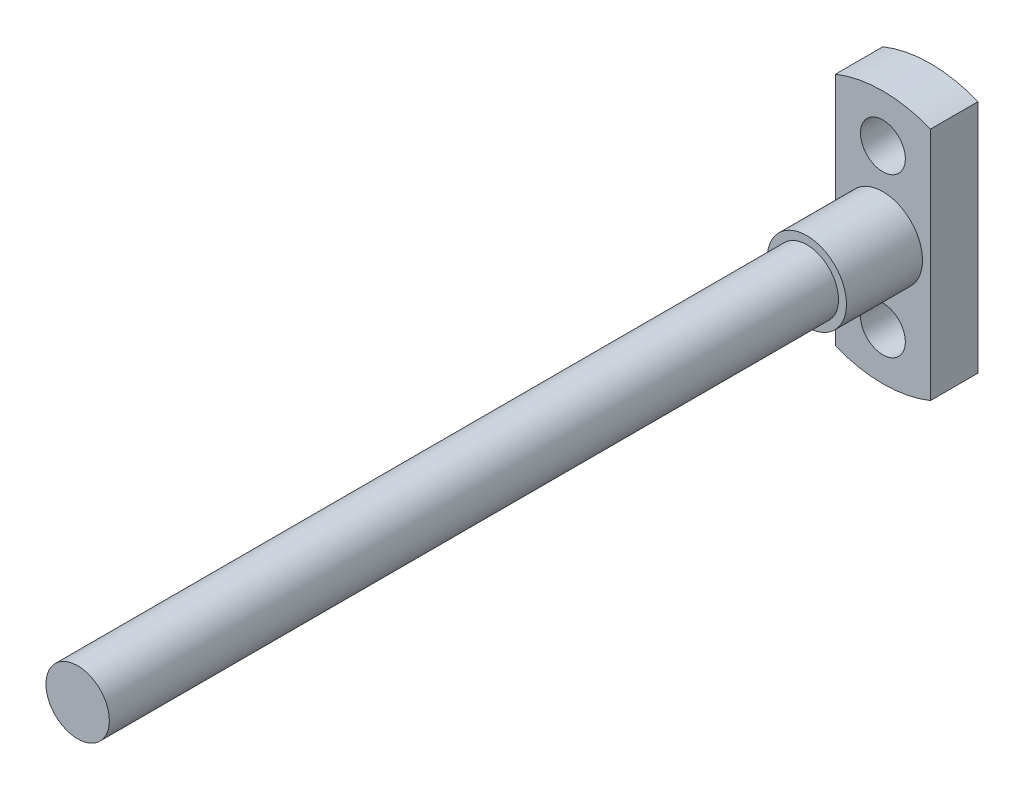
SolidWorks part; units mm, degrees
ref_plane "Front Plane" through (0, 0, 0) normal (0, 0, 1) x (1, 0, 0)
ref_plane "Top Plane" through (0, 0, 0) normal (0, 1, 0) x (1, 0, 0)
ref_plane "Right Plane" through (0, 0, 0) normal (1, 0, 0) x (0, 0, -1)
sketch "Sketch1" plane through (0, 0, 0) normal (0, 0, 1) x (1, 0, 0)
  line L0 (0, 0) -> (9.525, 23.5464) construction
  line L2 (0, 0) -> (0, 23.5464)
  line L4 (9.525, 0) -> (9.525, 23.5464)
  arc A0 (0, 23.5464) -> (9.525, 23.5464) centre (4.7625, 11.7732) cw
  arc A1 (9.525, 0) -> (0, 0) centre (4.7625, 11.7732) cw
  dimension "D1" = 12.7
  dimension "D2" = 9.525
extrude "Boss-Extrude1" add sketch "Sketch1" along normal blind 4.7625
sketch "Sketch2" plane through (0, 0, 4.7625) normal (0, 0, 1) x (1, 0, 0)
  line L0 (0, 23.5464) -> (9.525, 0) construction
  circle A0 centre (4.7625, 11.7732) radius 3.9688
  dimension "D1" = 7.9375
extrude "Boss-Extrude2" add sketch "Sketch2" along normal blind 7.62
sketch "Sketch3" plane through (0, 0, 12.3825) normal (0, 0, 1) x (1, 0, 0)
  circle A0 centre (4.7625, 11.7732) radius 3.175
  dimension "D1" = 6.35
extrude "Boss-Extrude3" add sketch "Sketch3" along normal blind 73.025
hole_wizard "#16 (0.177) Diameter Hole1" positions "Sketch5" profile "Sketch6" hole size "#16" standard "ANSI Inch" end condition through all
sketch "Sketch5" plane through (0, 0, 4.7625) normal (0, 0, 1) x (1, 0, 0)
  line L0 (4.7625, 24.4732) -> (4.7625, -0.9268) construction
  line L4 (0, 11.7732) -> (9.1829, 11.7732) construction
  line L5 (0, 23.5464) -> (0, 0) construction
  arc A1 (9.525, 23.5464) -> (0, 23.5464) centre (4.7625, 11.7732) ccw construction
  arc A2 (0, 0) -> (9.525, 0) centre (4.7625, 11.7732) ccw construction
  point P17 (4.7625, 3.8357)
  point P20 (4.7625, 19.7107)
  point P25 (0, 11.7732)
  dimension "D1" = 7.9375
sketch "Sketch6" plane through (4.7625, 3.8357, 4.7625) normal (1, 0, 0) x (0, -1, 0)
  line L0 (0, 0) -> (0, 4.7625)
  line L1 (0, 4.7625) -> (2.2479, 4.7625)
  line L2 (2.2479, 4.7625) -> (2.2479, 0)
  line L5 (2.2479, 0) -> (0, 0)
  line L11 (0, -6.35) -> (0, 107.95) construction
  dimension "Thru Hole Dia." = 4.4958
  dimension "Thru Hole Depth" = 4.7625
